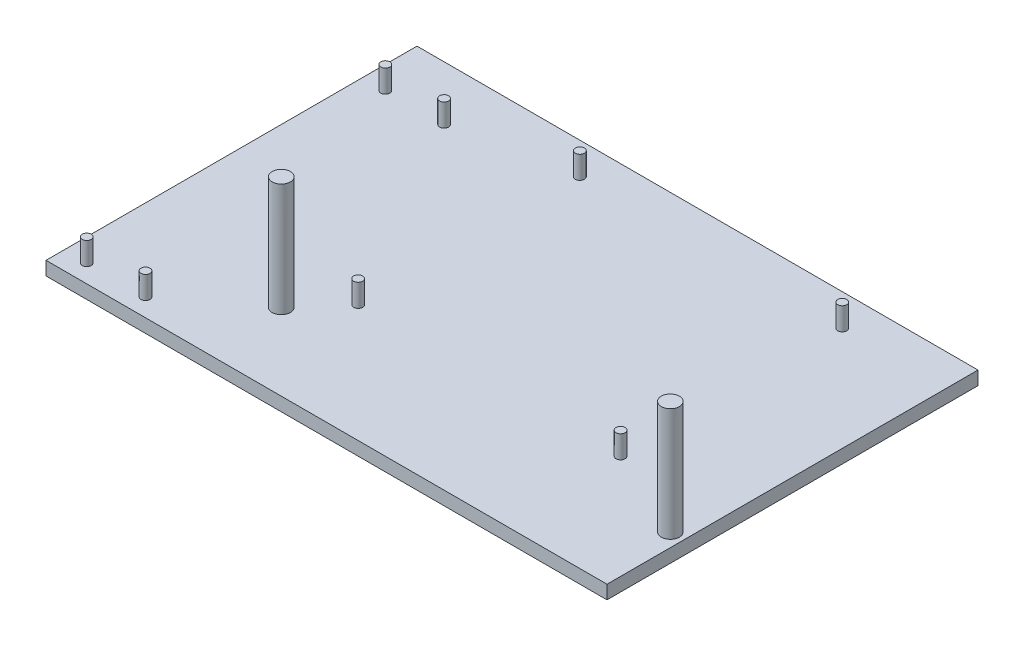
SolidWorks part; units mm, degrees
ref_plane "Front Plane" through (0, 0, 0) normal (0, 0, 1) x (1, 0, 0)
ref_plane "Top Plane" through (0, 0, 0) normal (0, 1, 0) x (1, 0, 0)
ref_plane "Right Plane" through (0, 0, 0) normal (1, 0, 0) x (0, 0, -1)
sketch "Sketch7" plane through (0, 0, 0) normal (0, 1, 0) x (1, 0, 0)
  line L0 (-62, 41) -> (62, 41)
  line L1 (62, 41) -> (62, -41)
  line L2 (62, -41) -> (-62, -41)
  line L3 (-62, -41) -> (-62, 41)
  point P2 (0, 41)
  point P5 (-62, 0)
  dimension "D1" = 82
  dimension "D2" = 124
extrude "Boss-Extrude3" add sketch "Sketch7" along normal blind 3
sketch "Sketch8" plane through (0, 3, 0) normal (0, 1, 0) x (1, 0, 0)
  line L0 (-62, -41) -> (62, -41) construction
  line L1 (62, -41) -> (62, 41) construction
  circle A0 centre (59, -24) radius 2
  circle A1 centre (-27, -24) radius 2
  point P6 (0, 0)
  dimension "D2" = 4
  dimension "D3" = 4
  dimension "D1" = 17
  dimension "D4" = 3
  dimension "D5" = 86
extrude "Boss-Extrude4" add sketch "Sketch8" along normal blind 25
sketch "Sketch9" plane through (0, 3, 0) normal (0, 1, 0) x (1, 0, 0)
  line L0 (62, -41) -> (62, 41) construction
  line L1 (62, 41) -> (-62, 41) construction
  circle A0 centre (39, 34) radius 1
  circle A1 centre (-19, 34) radius 1
  circle A2 centre (-19, -15) radius 1
  circle A3 centre (39, -15) radius 1
  point P8 (0, 0)
  point P9 (0, 0)
  point P10 (0, 0)
  point P11 (0, 0)
  dimension "D1" = 2
  dimension "D2" = 2
  dimension "D3" = 2
  dimension "D4" = 2
  dimension "D5" = 23
  dimension "D6" = 7
  dimension "D7" = 49
  dimension "D8" = 58
extrude "Boss-Extrude5" add sketch "Sketch9" along normal blind 5
sketch "Sketch10" plane through (0, 3, 0) normal (0, 1, 0) x (1, 0, 0)
  line L1 (-62, -41) -> (62, -41) construction
  line L2 (-62, 41) -> (-62, -41) construction
  circle A0 centre (-57, -37) radius 1
  circle A1 centre (-44, -37) radius 1
  circle A2 centre (-44, 29) radius 1
  circle A3 centre (-57, 29) radius 1
  point P8 (0, 0)
  point P9 (0, 0)
  point P10 (0, 0)
  point P11 (0, 0)
  dimension "D1" = 2
  dimension "D2" = 2
  dimension "D3" = 2
  dimension "D4" = 2
  dimension "D5" = 13
  dimension "D6" = 66
  dimension "D7" = 4
  dimension "D8" = 5
extrude "Boss-Extrude6" add sketch "Sketch10" along normal blind 5
